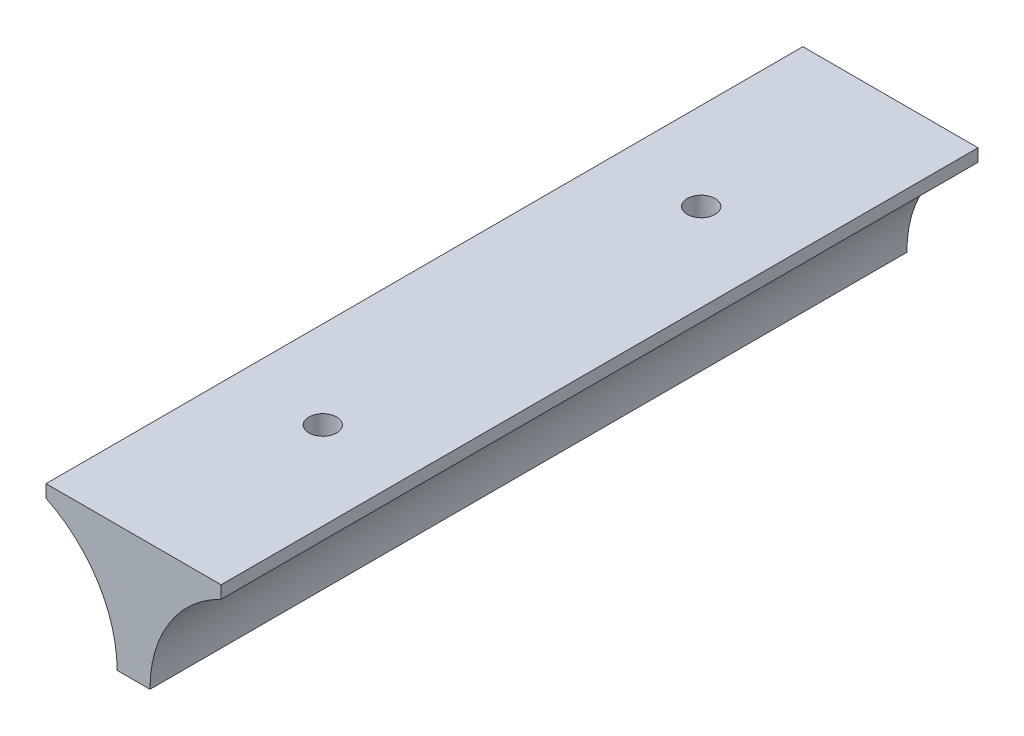
SolidWorks part; units mm, degrees
ref_plane "Front" through (0, 0, 0) normal (0, 0, 1) x (1, 0, 0)
ref_plane "Top" through (0, 0, 0) normal (0, 1, 0) x (1, 0, 0)
ref_plane "Right" through (0, 0, 0) normal (1, 0, 0) x (0, 0, -1)
sketch "Sketch1" plane through (0, 0, 0) normal (0, 0, 1) x (1, 0, 0)
  line L0 (-1.3, 0) -> (1.3, 0)
  line L1 (6.9411, 9) -> (6.9411, 10)
  line L2 (6.9411, 10) -> (-6.9411, 10)
  line L3 (-6.9411, 10) -> (-6.9411, 9)
  arc A0 (1.3, 0) -> (6.9411, 9) centre (11.3, 0) cw
  arc A1 (-1.3, 0) -> (-6.9411, 9) centre (-11.3, 0) ccw
  point P9 (0, 0)
  point P10 (0, 10)
  dimension "D1" = 10
  dimension "D2" = 10
  dimension "D3" = 2.6
  dimension "D4" = 1
extrude "Boss-Extrude1" add sketch "Sketch1" along normal mid plane 60
sketch "Sketch2" plane through (0, 10, 0) normal (0, 1, 0) x (1, 0, 0)
  line L0 (0, -30) -> (0, 30) construction
  line L1 (6.9411, -30) -> (-6.9411, -30) construction
  line L2 (6.9411, 30) -> (-6.9411, 30) construction
  point P6 (0, -15)
  point P7 (0, 15)
  dimension "D1" = 15
  dimension "D2" = 15
hole_wizard "Ø2.2 (2.2) Diameter Hole1" positions "3DSketch1" profile "Sketch3" hole size "Ø2.2" standard "ANSI Metric" end condition up to next
sketch3d "3DSketch1"
  point P0 (0, 10, 15)
  point P3 (0, 10, -15)
sketch "Sketch3" plane through (0, 10, 15) normal (1, 0, 0) x (0, 0, 1)
  line L0 (0, 0) -> (0, 10)
  line L1 (0, 10) -> (1.1, 10)
  line L2 (1.1, 10) -> (1.1, 0)
  line L5 (1.1, 0) -> (0, 0)
  line L11 (0, -6.35) -> (0, 107.95) construction
  dimension "Thru Hole Dia." = 2.2
  dimension "Thru Hole Depth" = 10
